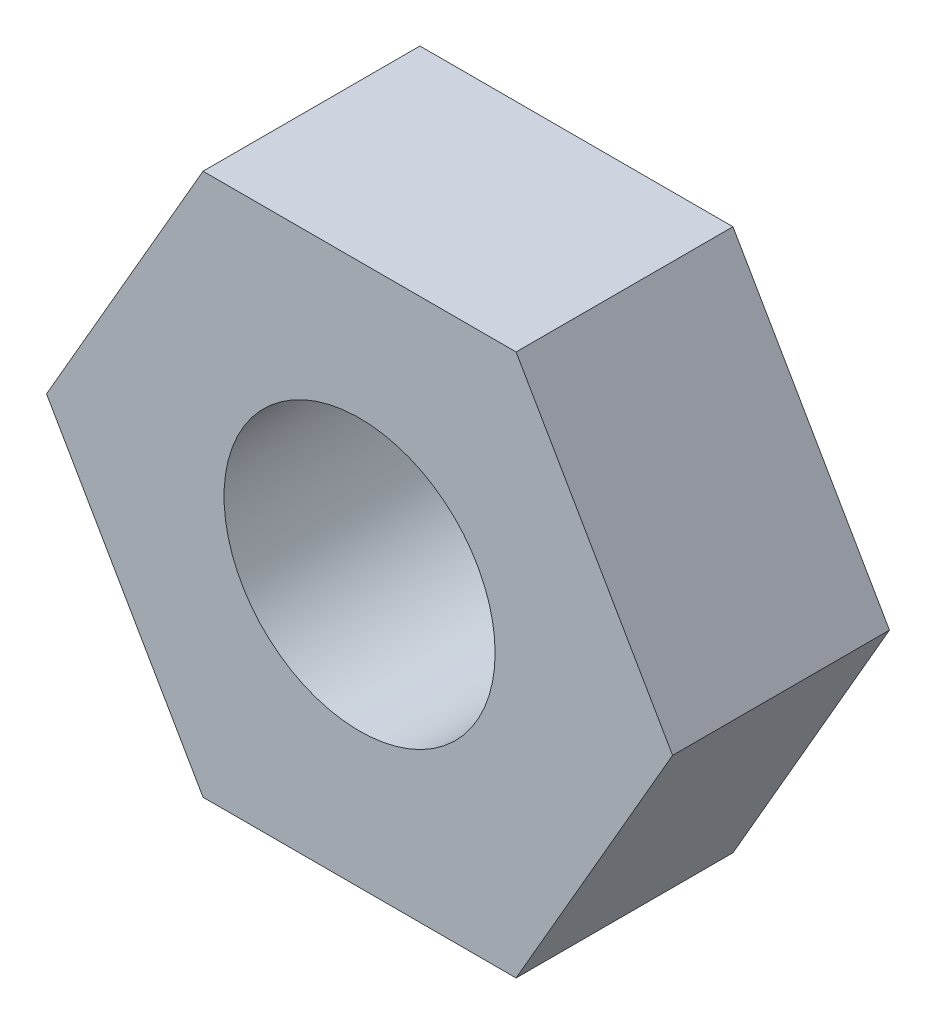
SolidWorks part; units mm, degrees
ref_plane "Front Plane" through (0, 0, 0) normal (0, 0, 1) x (1, 0, 0)
ref_plane "Top Plane" through (0, 0, 0) normal (0, 1, 0) x (1, 0, 0)
ref_plane "Right Plane" through (0, 0, 0) normal (1, 0, 0) x (0, 0, -1)
sketch "Across_flats_4" plane through (0, 0, 0) normal (0, 0, 1) x (1, 0, 0)
  line L0 (2.3094, 0) -> (1.1547, 2)
  line L1 (1.1547, 2) -> (-1.1547, 2)
  line L2 (-1.1547, 2) -> (-2.3094, 0)
  line L3 (-2.3094, 0) -> (-1.1547, -2)
  line L4 (-1.1547, -2) -> (1.1547, -2)
  line L5 (1.1547, -2) -> (2.3094, 0)
  circle A0 centre (0, 0) radius 1
  dimension "D1" = 2
extrude "Nut_thread_envelope_height_1.6" add sketch "Across_flats_4" along normal blind 1.6
